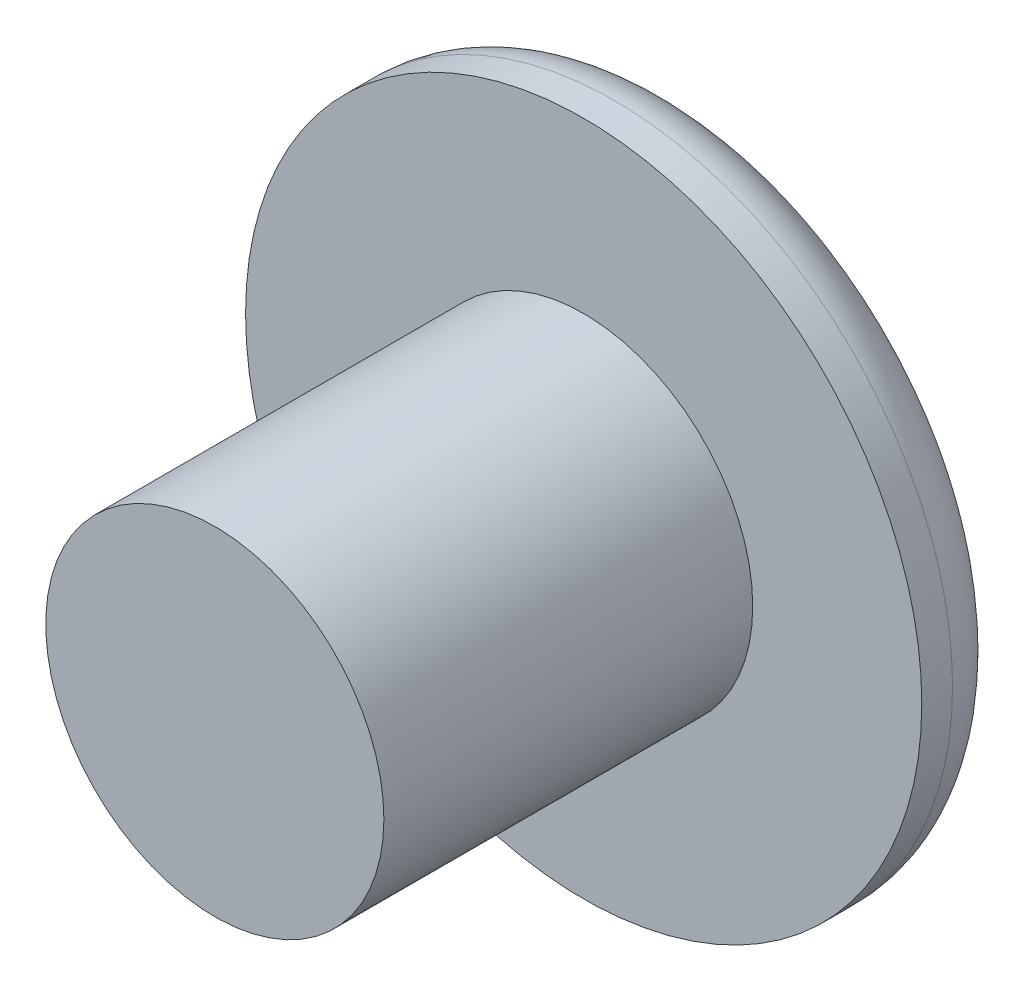
SolidWorks part; units mm, degrees
ref_plane "Front Plane" through (0, 0, 0) normal (0, 0, 1) x (1, 0, 0)
ref_plane "Top Plane" through (0, 0, 0) normal (0, 1, 0) x (1, 0, 0)
ref_plane "Right Plane" through (0, 0, 0) normal (1, 0, 0) x (0, 0, -1)
sketch "Sketch1" plane through (0, 0, 0) normal (0, 0, 1) x (1, 0, 0)
  circle A0 centre (0, 0) radius 11
  dimension "D1" = 22
extrude "Boss-Extrude1" add sketch "Sketch1" along normal blind 3
sketch "Sketch2" plane through (0, 0, 3) normal (0, 0, 1) x (1, 0, 0)
  circle A0 centre (0, 0) radius 5.5
extrude "Boss-Extrude2" add sketch "Sketch2" along normal blind 12
fillet "Fillet2" radius 2 1 edges at (11, 0, 0)
